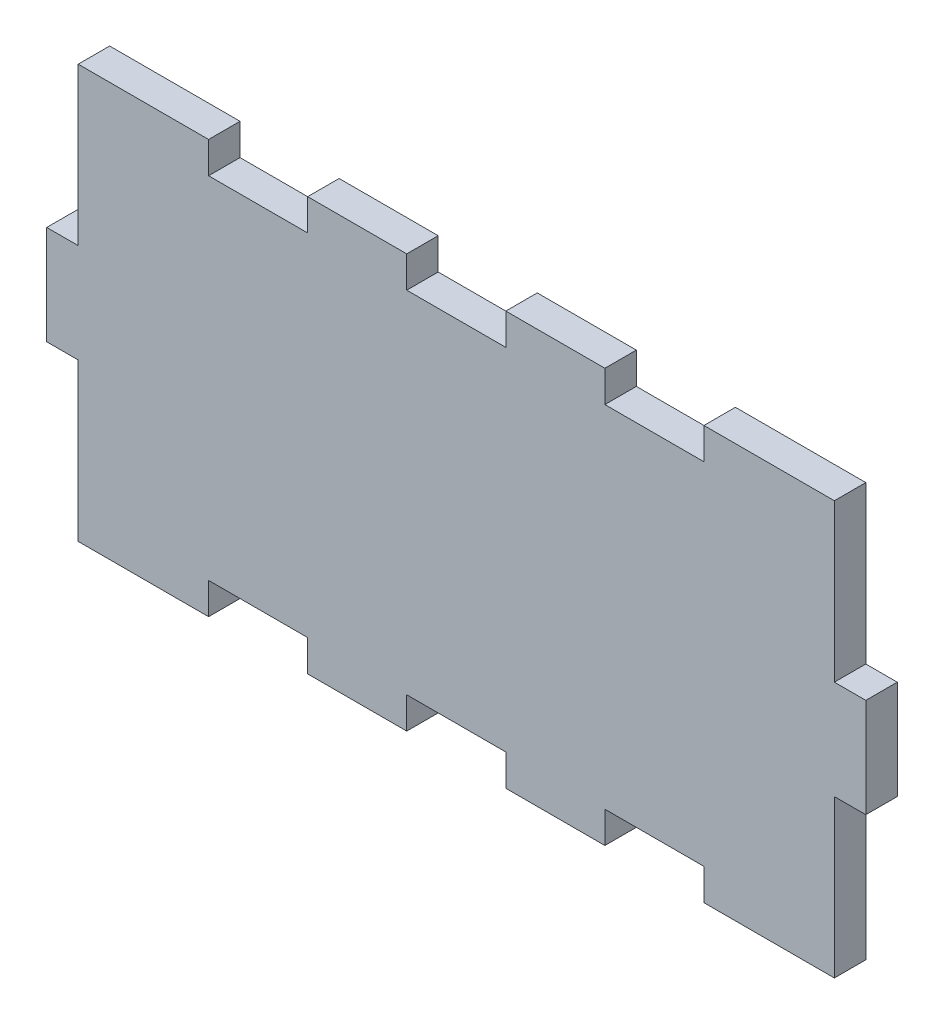
SolidWorks part; units mm, degrees
ref_plane "Plan de face" through (0, 0, 0) normal (0, 0, 1) x (1, 0, 0)
ref_plane "Plan de dessus" through (0, 0, 0) normal (0, 1, 0) x (1, 0, 0)
ref_plane "Plan de droite" through (0, 0, 0) normal (1, 0, 0) x (0, 0, -1)
sketch "Esquisse1" plane through (0, 0, 0) normal (0, 0, 1) x (1, 0, 0)
  line L0 (-82.675, 41.7195) -> (-82.675, -41.7195)
  line L1 (-82.675, 41.7195) -> (82.675, 41.7195)
  line L3 (-82.675, -41.7195) -> (82.675, -41.7195)
  line L4 (82.675, 41.7195) -> (82.675, -41.7195)
  point P4 (0, -41.7195)
  point P6 (82.675, 0)
  point P7 (-82.675, 0)
  dimension "D1" = 83.439
  dimension "D2" = 165.35
extrude "Boss.-Extru.1" add sketch "Esquisse1" along normal blind 6.35
sketch "Esquisse4" plane through (0, 0, 6.35) normal (0, 0, 1) x (1, 0, 0)
  line L0 (-82.675, 41.7195) -> (-82.675, -41.7195) construction
  line L1 (-82.675, 10) -> (-76.325, 10)
  line L2 (-82.675, 10) -> (-82.675, -10)
  line L3 (-82.675, -10) -> (-76.325, -10)
  line L4 (-76.325, 10) -> (-76.325, -10)
  point P6 (-76.325, 0)
  dimension "D1" = 20
  dimension "D2" = 6.35
sketch "Esquisse2" plane through (0, 0, 6.35) normal (0, 0, 1) x (1, 0, 0)
  line L0 (-82.675, 41.7195) -> (-82.675, -41.7195) construction
  line L1 (-82.675, -41.7195) -> (-76.325, -41.7195)
  line L2 (-82.675, -41.7195) -> (-82.675, -10)
  line L3 (-82.675, -10) -> (-76.325, -10)
  line L4 (-76.325, -41.7195) -> (-76.325, -10)
  line L9 (-82.675, 10) -> (-76.325, 10)
  line L10 (-82.675, 10) -> (-82.675, 41.7195)
  line L11 (-82.675, 41.7195) -> (-76.325, 41.7195)
  line L12 (-76.325, 10) -> (-76.325, 41.7195)
  line L13 (-82.675, -41.7195) -> (82.675, -41.7195) construction
  line L14 (-82.675, 10) -> (-76.325, 10) construction
  line L15 (82.675, 41.7195) -> (-82.675, 41.7195) construction
  line L16 (-82.675, -10) -> (-76.325, -10) construction
  dimension "D1" = 6.35
extrude "Enlèv. mat.-Extru.1" cut sketch "Esquisse2" against normal through all
mirror "Symétrie1" about plane through (0, 0, 0) normal (1, 0, 0) of "Enlèv. mat.-Extru.1"
sketch "Esquisse3" plane through (0, 0, 6.35) normal (0, 0, 1) x (1, 0, 0)
  line L0 (-76.325, -41.7195) -> (76.325, -41.7195) construction
  line L1 (-10, -41.7195) -> (10, -41.7195)
  line L2 (-10, -41.7195) -> (-10, -35.3695)
  line L3 (-10, -35.3695) -> (10, -35.3695)
  line L4 (10, -41.7195) -> (10, -35.3695)
  line L6 (30, -41.7195) -> (50, -41.7195)
  line L7 (30, -41.7195) -> (30, -35.3695)
  line L8 (30, -35.3695) -> (50, -35.3695)
  line L9 (50, -41.7195) -> (50, -35.3695)
  line L10 (-30, -41.7195) -> (-50, -41.7195)
  line L11 (-30, -41.7195) -> (-30, -35.3695)
  line L12 (-30, -35.3695) -> (-50, -35.3695)
  line L13 (-50, -41.7195) -> (-50, -35.3695)
  point P14 (0, -35.3695)
  point P16 (30, -38.5445)
  point P17 (10, -38.5445)
  dimension "D1" = 20
  dimension "D2" = 20
  dimension "D3" = 20
  dimension "D4" = 6.35
extrude "Enlèv. mat.-Extru.2" cut sketch "Esquisse3" against normal through all
mirror "Symétrie2" about plane through (0, 0, 0) normal (0, 1, 0) of "Enlèv. mat.-Extru.2"
